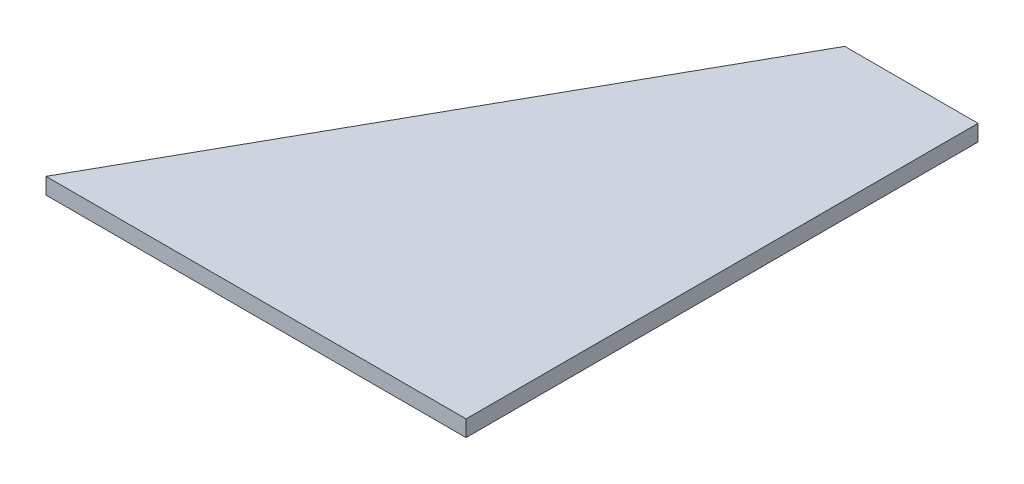
SolidWorks part; units mm, degrees
ref_plane "Front Plane" through (0, 0, 0) normal (0, 0, 1) x (1, 0, 0)
ref_plane "Top Plane" through (0, 0, 0) normal (0, 1, 0) x (1, 0, 0)
ref_plane "Right Plane" through (0, 0, 0) normal (1, 0, 0) x (0, 0, -1)
sketch "Sketch1" plane through (0, 0, 0) normal (0, 1, 0) x (1, 0, 0)
  line L0 (-49.4304, 66.0459) -> (32.5696, 66.0459)
  line L2 (32.5696, -248.9541) -> (-225.903, -248.9541)
  line L3 (-225.903, -248.9541) -> (-49.4304, 66.0459)
  line L4 (32.5696, 66.0459) -> (32.5696, -248.9541)
  dimension "D1" = 82
  dimension "D2" = 315
extrude "Boss-Extrude1" add sketch "Sketch1" along normal blind 10
